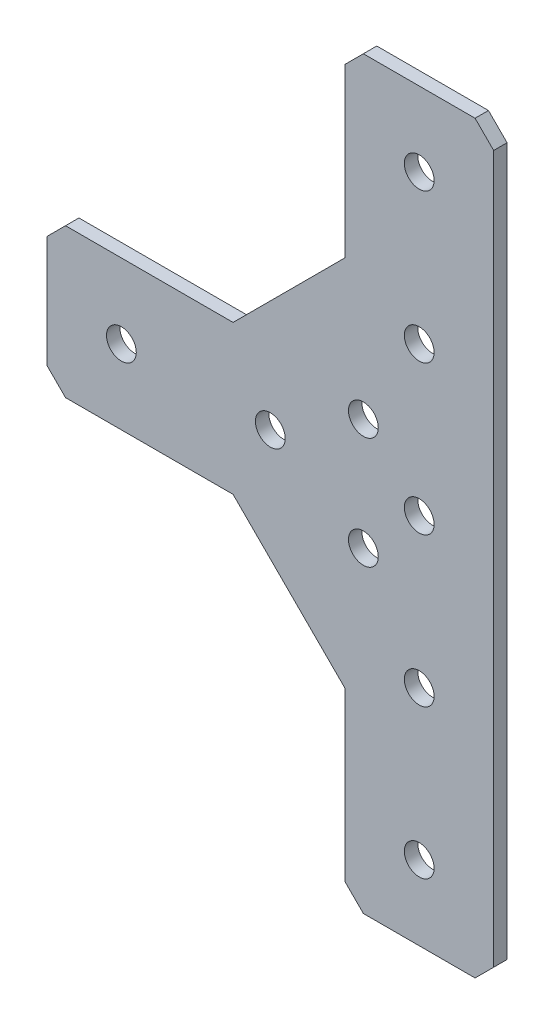
SolidWorks part; units mm, degrees
material "6063-T5"
ref_plane "Front Plane" through (0, 0, 0) normal (0, 0, 1) x (1, 0, 0)
ref_plane "Top Plane" through (0, 0, 0) normal (0, 1, 0) x (1, 0, 0)
ref_plane "Right Plane" through (0, 0, 0) normal (1, 0, 0) x (0, 0, -1)
ref_plane "Plane1" through (0, 0, -2.286) normal (0, 0, -1) x (-1, 0, 0)
sketch "Sketch1" plane through (0, 0, -2.286) normal (0, 0, -1) x (-1, 0, 0)
  line L0 (31.75, -12.7) -> (60.325, -12.7)
  line L1 (60.325, -12.7) -> (63.5, -9.525)
  line L2 (63.5, -9.525) -> (63.5, 9.525)
  line L3 (63.5, 9.525) -> (60.325, 12.7)
  line L4 (60.325, 12.7) -> (31.75, 12.7)
  line L5 (31.75, 12.7) -> (12.7, 31.75)
  line L6 (12.7, 31.75) -> (12.7, 60.325)
  line L7 (12.7, 60.325) -> (9.525, 63.5)
  line L8 (9.525, 63.5) -> (-9.525, 63.5)
  line L9 (-9.525, 63.5) -> (-12.7, 60.325)
  line L10 (-12.7, 60.325) -> (-12.7, -60.325)
  line L11 (-12.7, -60.325) -> (-9.525, -63.5)
  line L12 (-9.525, -63.5) -> (9.525, -63.5)
  line L13 (9.525, -63.5) -> (12.7, -60.325)
  line L14 (12.7, -60.325) -> (12.7, -31.75)
  line L15 (12.7, -31.75) -> (31.75, -12.7)
  circle A0 centre (0, -50.8) radius 2.54
  circle A1 centre (0, -25.4) radius 2.54
  circle A2 centre (0, 0) radius 2.54
  circle A3 centre (0, 50.8) radius 2.54
  circle A4 centre (0, 25.4) radius 2.54
  circle A5 centre (50.8, 0) radius 2.54
  circle A6 centre (25.4, 0) radius 2.54
  circle A7 centre (9.525, -9.525) radius 2.54
  circle A8 centre (9.525, 9.525) radius 2.54
extrude "Boss-Extrude1" add sketch "Sketch1" against normal blind 2.286
